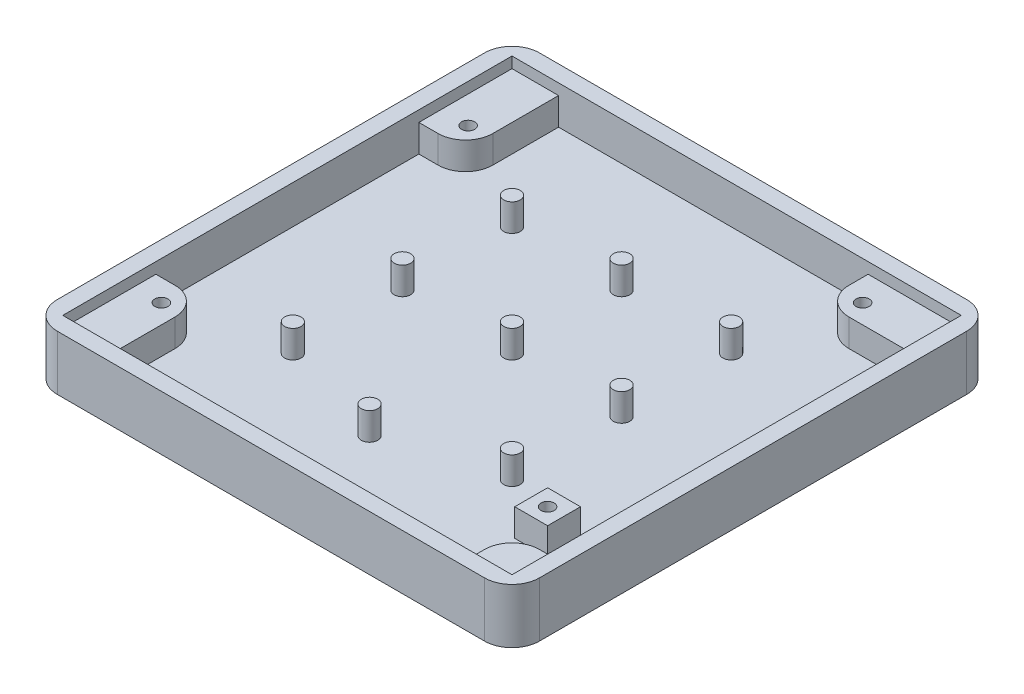
SolidWorks part; units mm, degrees
ref_plane "前基準面" through (0, 0, 0) normal (0, 0, 1) x (1, 0, 0)
ref_plane "上基準面" through (0, 0, 0) normal (0, 1, 0) x (1, 0, 0)
ref_plane "右基準面" through (0, 0, 0) normal (1, 0, 0) x (0, 0, -1)
sketch "草圖1" plane through (0, 0, 0) normal (0, 1, 0) x (1, 0, 0)
  line L1 (-36.3708, 38.0118) -> (51.6292, 38.0118)
  line L2 (-36.3708, 38.0118) -> (-36.3708, -49.9882)
  line L3 (-36.3708, -49.9882) -> (51.6292, -49.9882)
  line L4 (51.6292, 38.0118) -> (51.6292, -49.9882)
  dimension "D1" = 88
  dimension "D2" = 88
extrude "填料-伸長1" add sketch "草圖1" along normal blind 3
sketch "草圖2" plane through (0, 3, 0) normal (0, 1, 0) x (1, 0, 0)
  line L0 (-36.3708, 38.0118) -> (-36.3708, -49.9882)
  line L1 (-36.3708, -49.9882) -> (51.6292, -49.9882)
  line L2 (51.6292, -49.9882) -> (51.6292, 38.0118)
  line L3 (51.6292, 38.0118) -> (-36.3708, 38.0118)
  line L4 (-33.3708, 35.0118) -> (-33.3708, -46.9882)
  line L5 (-33.3708, -46.9882) -> (48.6292, -46.9882)
  line L6 (48.6292, -46.9882) -> (48.6292, 35.0118)
  line L7 (48.6292, 35.0118) -> (-33.3708, 35.0118)
  dimension "D1" = 3
  dimension "D2" = 3
  dimension "D3" = 3
  dimension "D4" = 3
extrude "填料-伸長2" add sketch "草圖2" along normal blind 7
sketch "草圖3" plane through (0, 3, 0) normal (0, 1, 0) x (1, 0, 0)
  line L0 (-33.3708, 35.0118) -> (-33.3708, -46.9882) construction
  line L1 (-33.3708, 35.0118) -> (-24.8708, 35.0118)
  line L2 (-33.3708, 35.0118) -> (-33.3708, 18.0118)
  line L3 (-33.3708, 18.0118) -> (-24.8708, 18.0118)
  line L4 (-24.8708, 35.0118) -> (-24.8708, 18.0118)
  line L5 (-33.3708, -46.9882) -> (-24.8708, -46.9882)
  line L6 (-33.3708, -46.9882) -> (-33.3708, -29.9882)
  line L7 (-33.3708, -29.9882) -> (-24.8708, -29.9882)
  line L8 (-24.8708, -46.9882) -> (-24.8708, -29.9882)
  line L9 (48.6292, 35.0118) -> (31.6292, 35.0118)
  line L10 (48.6292, 35.0118) -> (48.6292, 26.5118)
  line L11 (48.6292, 26.5118) -> (31.6292, 26.5118)
  line L12 (31.6292, 35.0118) -> (31.6292, 26.5118)
  line L13 (48.6292, -46.9882) -> (40.1292, -46.9882)
  line L14 (48.6292, -46.9882) -> (48.6292, -38.4882)
  line L15 (48.6292, -38.4882) -> (40.1292, -38.4882)
  line L16 (40.1292, -46.9882) -> (40.1292, -38.4882)
  line L22 (-33.3708, 35.0118) -> (-33.3708, -46.9882) construction
  line L26 (48.6292, 35.0118) -> (-33.3708, 35.0118) construction
  line L27 (36.1292, -27.9882) -> (42.1292, -27.9882)
  line L28 (36.1292, -27.9882) -> (36.1292, -33.9882)
  line L29 (36.1292, -33.9882) -> (42.1292, -33.9882)
  line L30 (42.1292, -27.9882) -> (42.1292, -33.9882)
  line L47 (48.6292, -46.9882) -> (48.6292, 35.0118) construction
  line L49 (-33.3708, -46.9882) -> (48.6292, -46.9882) construction
  line L50 (48.6292, -46.9882) -> (48.6292, 35.0118) construction
  circle A4 centre (-28.3708, 22.0118) radius 1.2
  circle A5 centre (-28.3708, -33.9882) radius 1.2
  circle A6 centre (35.6292, 30.0118) radius 1.2
  circle A7 centre (39.1292, -30.9882) radius 1.2
  circle A8 centre (-13.3708, 15.0118) radius 1.5
  circle A9 centre (6.6292, 15.0118) radius 1.5
  circle A10 centre (26.6292, 15.0118) radius 1.5
  circle A11 centre (6.6292, -4.9882) radius 1.5
  circle A12 centre (26.6292, -4.9882) radius 1.5
  circle A14 centre (26.6292, -24.9882) radius 1.5
  circle A15 centre (-13.3708, -4.9882) radius 1.5
  circle A16 centre (-13.3708, -24.9882) radius 1.5
  circle A17 centre (6.6292, -24.9882) radius 1.5 [skipped]
  circle A18 centre (6.6292, -30.9882) radius 1.5
  point P52 (39.1292, -33.9882)
  dimension "D9" = 3
  dimension "D10" = 13
  dimension "D30" = 3
  dimension "D31" = 5
  dimension "D34" = 20
  dimension "D38" = 3
  dimension "D12" = 2.4
  dimension "D11" = 13
  dimension "D13" = 16
  dimension "D14" = 9.5
  dimension "D1" = 8.5
  dimension "D2" = 17
  dimension "D3" = 8.5
  dimension "D4" = 17
  dimension "D5" = 8.5
  dimension "D6" = 17
  dimension "D7" = 8.5
  dimension "D8" = 8.5
  dimension "D15" = 13
  dimension "D27" = 6
  dimension "D28" = 6
  dimension "D29" = 3
  dimension "D32" = 5
  dimension "D33" = 5
  dimension "D35" = 20
  dimension "D39" = 40
  dimension "D36" = 3
  dimension "D37" = 3
extrude "填料-伸長3" add sketch "草圖3" along normal blind 5
fillet "圓角1" radius 5 8 edges at (51.6292, 5, -38.0118) (51.6292, 5, 49.9882) (-36.3708, 5, 49.9882) (-36.3708, 5, -38.0118) (40.1292, 5.5, 38.4882) (-24.8708, 5.5, 29.9882) (31.6292, 5.5, -26.5118) (-24.8708, 5.5, -18.0118)
